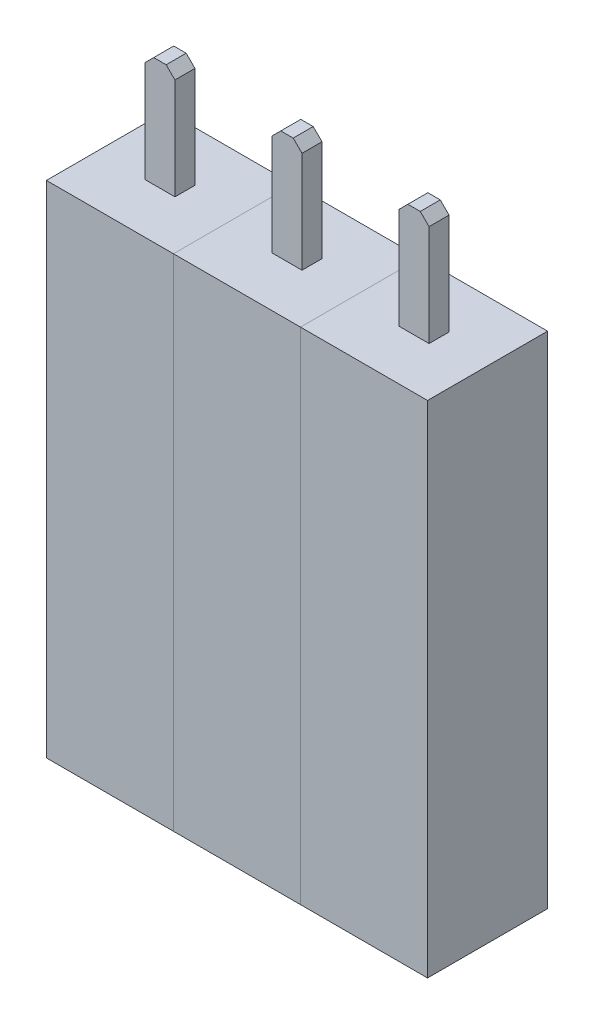
SolidWorks part; units mm, degrees
ref_plane "Front Plane" through (0, 0, 0) normal (0, 0, 1) x (1, 0, 0)
ref_plane "Top Plane" through (0, 0, 0) normal (0, 1, 0) x (1, 0, 0)
ref_plane "Right Plane" through (0, 0, 0) normal (1, 0, 0) x (0, 0, -1)
sketch "Sketch1" plane through (0, 0, 0) normal (0, 0, 1) x (1, 0, 0)
  line L1 (-1.27, 5) -> (1.27, 5)
  line L2 (-1.27, 5) -> (-1.27, -5)
  line L3 (-1.27, -5) -> (1.27, -5)
  line L4 (1.27, 5) -> (1.27, -5)
  line L5 (-1.27, 5) -> (1.27, -5) construction
  line L6 (-1.27, -5) -> (1.27, 5) construction
  point P0 (0, 0)
  dimension "D1" = 2.54
  dimension "D2" = 10
extrude "Boss-Extrude1" add sketch "Sketch1" along normal mid plane 2.4
sketch "Sketch2" plane through (0, -5, 0) normal (0, -1, 0) x (1, 0, 0)
  line L0 (0, -1.2) -> (0, 1.2) construction
  line L1 (-1.27, 1.2) -> (1.27, 1.2) construction
  line L2 (-1.27, -1.2) -> (1.27, -1.2) construction
  line L4 (-0.6, 0.6) -> (0.6, 0.6)
  line L5 (-0.6, 0.6) -> (-0.6, -0.6)
  line L6 (-0.6, -0.6) -> (0.6, -0.6)
  line L7 (0.6, 0.6) -> (0.6, -0.6)
  line L8 (-0.6, 0.6) -> (0.6, -0.6) construction
  line L9 (-0.6, -0.6) -> (0.6, 0.6) construction
  point P5 (0, 0)
  dimension "D1" = 1.2
extrude "Cut-Extrude1" cut sketch "Sketch2" against normal blind 7
sketch "Sketch3" plane through (0, 0, 0) normal (0, 0, 1) x (1, 0, 0)
  line L0 (-0.3, 5) -> (-0.3, 7.0243)
  line L1 (1.27, 5) -> (-1.27, 5) construction
  line L2 (-0.3, 7.0243) -> (-0.1243, 7.2)
  line L3 (-0.1243, 7.2) -> (0.1243, 7.2)
  line L4 (0, 7.2) -> (0, 5) construction
  line L5 (-0.3, 5) -> (0.3, 5)
  line L6 (0.3, 7.0243) -> (0.1243, 7.2)
  line L7 (0.3, 5) -> (0.3, 7.0243)
  dimension "D1" = 0.6
  dimension "D2" = 45
  dimension "D3" = 2.2
extrude "Boss-Extrude2" add sketch "Sketch3" along normal mid plane 0.4
pattern_linear "LPattern1" count 3 spacing 2.54 along (1, 0, 0) of bodies 103
